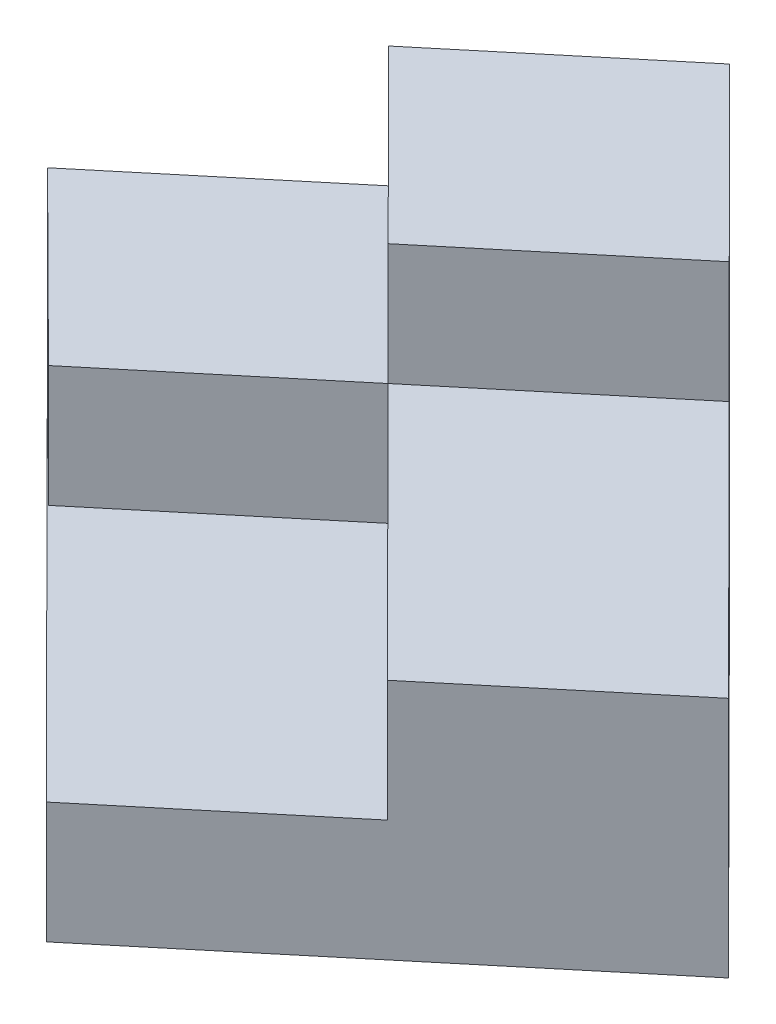
SolidWorks part; units mm, degrees
ref_plane "Front Plane" through (0, 0, 0) normal (0, 0, 1) x (1, 0, 0)
ref_plane "Top Plane" through (0, 0, 0) normal (0, 1, 0) x (1, 0, 0)
ref_plane "Right Plane" through (0, 0, 0) normal (1, 0, 0) x (0, 0, -1)
sketch "Sketch1" plane through (0, 0, 0) normal (0, 1, 0) x (1, 0, 0)
  line L0 (0, 0) -> (35.3021, -35.4085)
  line L1 (0, 0) -> (-30.75, -25.582)
  line L2 (35.3021, -35.4085) -> (4.5521, -60.9904)
  line L3 (-30.75, -25.582) -> (4.5521, -60.9904)
  dimension "D1" = 50
  dimension "D2" = 40
extrude "Boss-Extrude1" add sketch "Sketch1" along normal blind 10
sketch "Sketch2" plane through (0, 10, 0) normal (0, 1, 0) x (1, 0, 0)
  line L0 (-30.75, -25.582) -> (-15.375, -12.791)
  line L1 (-30.75, -25.582) -> (-16.5695, -39.6856)
  line L2 (-15.375, -12.791) -> (-1.1945, -26.8946)
  line L3 (-16.5695, -39.6856) -> (-1.1945, -26.8946)
  line L4 (0, 0) -> (-30.75, -25.582) construction
  line L5 (-15.375, -12.791) -> (0, 0)
  line L6 (-15.375, -12.791) -> (-1.2542, -26.9544)
  line L7 (0, 0) -> (14.1209, -14.1634)
  line L8 (-1.2542, -26.9544) -> (14.1209, -14.1634)
  line L9 (35.3021, -35.4085) -> (0, 0) construction
  line M9 (0, 0) -> (-30.75, -25.582)
extrude "Boss-Extrude2" add sketch "Sketch2" along normal blind 10 contours L6 L1 L3 M9
sketch "Sketch3" plane through (0, 0, 0) normal (0, 1, 0) x (1, 0, 0)
  line L0 (0, 0) -> (-15.375, -12.791)
  line L1 (0, 0) -> (14.1153, -14.1579)
  line L2 (-15.375, -12.791) -> (-1.2597, -26.9488)
  line L3 (14.1153, -14.1579) -> (-1.2597, -26.9488)
extrude "Boss-Extrude3" add sketch "Sketch3" along normal blind 30
sketch "Sketch4" plane through (0, 0, 0) normal (0, 1, 0) x (1, 0, 0)
  line L0 (14.1153, -14.1579) -> (-1.2597, -26.9488)
  line L1 (14.1153, -14.1579) -> (35.3021, -35.4085)
  line L2 (-1.2597, -26.9488) -> (19.9271, -48.1994)
  line L3 (35.3021, -35.4085) -> (19.9271, -48.1994)
  line L4 (4.5521, -60.9904) -> (35.3021, -35.4085) construction
extrude "Boss-Extrude5" add sketch "Sketch4" along normal blind 20
